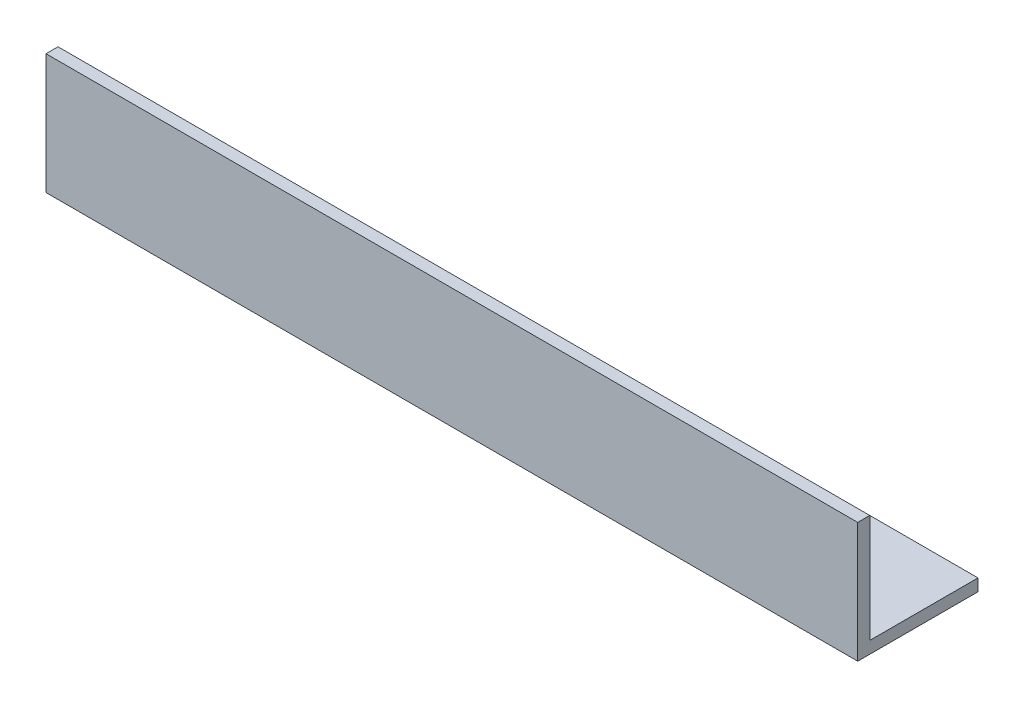
SolidWorks part; units mm, degrees
ref_plane "Front Plane" through (0, 0, 0) normal (0, 0, 1) x (1, 0, 0)
ref_plane "Top Plane" through (0, 0, 0) normal (0, 1, 0) x (1, 0, 0)
ref_plane "Right Plane" through (0, 0, 0) normal (1, 0, 0) x (0, 0, -1)
sketch "Sketch1" plane through (0, 0, 0) normal (1, 0, 0) x (0, 0, -1)
  line L0 (0, 20) -> (0, 0)
  line L1 (0, 0) -> (20, 0)
  line L2 (20, 0) -> (20, 2)
  line L3 (20, 2) -> (2, 2)
  line L4 (2, 2) -> (2, 20)
  line L5 (2, 20) -> (0, 20)
  dimension "D1" = 20
  dimension "D2" = 20
  dimension "D3" = 2
  dimension "D4" = 2
extrude "Boss-Extrude1" add sketch "Sketch1" along normal blind 135
sketch "Sketch2" plane through (0, 2, 0) normal (0, 1, 0) x (1, 0, 0)
  line L0 (135, 20) -> (0, 20) construction
  line L1 (0, 20) -> (0, 2) construction
  circle A0 centre (8, 11) radius 2.5
  circle A1 centre (30, 11) radius 2.5
  dimension "D3" = 5
  dimension "D4" = 5
  dimension "D1" = 9
  dimension "D2" = 8
  dimension "D5" = 30
extrude "Cut-Extrude1" cut sketch "Sketch2" against normal blind 2
